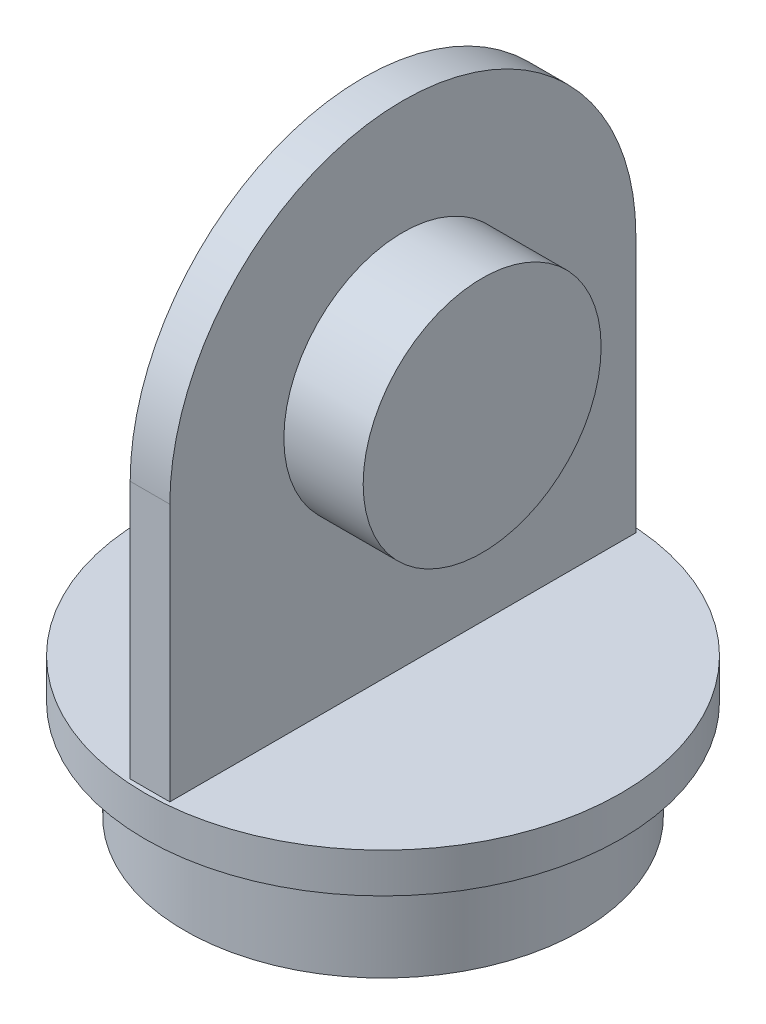
SolidWorks part; units mm, degrees
ref_plane "Front Plane" through (0, 0, 0) normal (0, 0, 1) x (1, 0, 0)
ref_plane "Top Plane" through (0, 0, 0) normal (0, 1, 0) x (1, 0, 0)
ref_plane "Right Plane" through (0, 0, 0) normal (1, 0, 0) x (0, 0, -1)
sketch "Sketch1" plane through (0, 0, 0) normal (0, 1, 0) x (1, 0, 0)
  circle A0 centre (0, 0) radius 12
  dimension "D1" = 24
extrude "Boss-Extrude1" add sketch "Sketch1" along normal blind 2
sketch "Sketch2" plane through (0, 0, 0) normal (1, 0, 0) x (0, 0, -1)
  line L0 (-11.75, 2) -> (-11.75, 15)
  line L1 (12, 2) -> (-12, 2) construction
  line L2 (11.75, 15) -> (11.75, 2)
  line L3 (-11.75, 2) -> (11.75, 2)
  arc A0 (-11.75, 15) -> (11.75, 15) centre (0, 15) cw
  dimension "D1" = 13
  dimension "D2" = 0.25
  dimension "D3" = 0.25
extrude "Boss-Extrude2" add sketch "Sketch2" along normal mid plane 2
sketch "Sketch3" plane through (0, 0, 0) normal (0, -1, 0) x (1, 0, 0)
  circle A0 centre (0, 0) radius 10
  dimension "D1" = 20
extrude "Boss-Extrude3" add sketch "Sketch3" along normal blind 5
sketch "Sketch5" plane through (0, 0, 0) normal (1, 0, 0) x (0, 0, -1)
  circle A0 centre (0, 15) radius 6
  dimension "D1" = 12
extrude "Boss-Extrude6" add sketch "Sketch5" along normal mid plane 10
scale "Scale1" bodies to scale 106 scale about centroid uniform scaling yes scale factor 2
